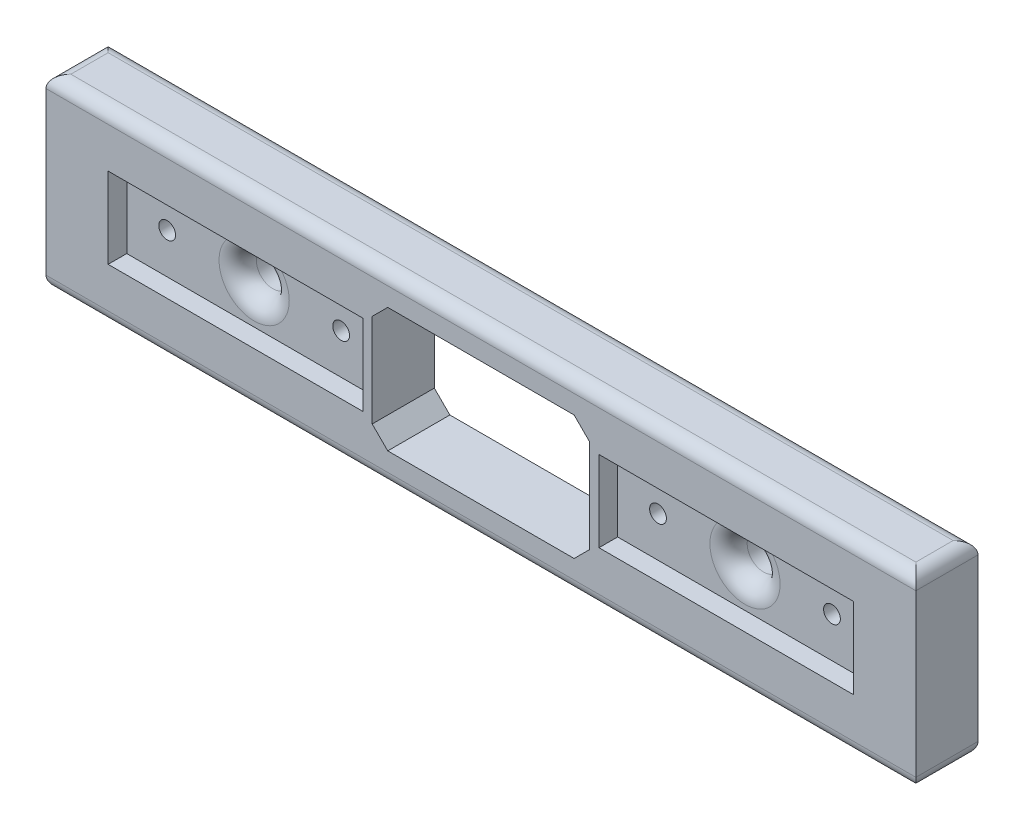
SolidWorks part; units mm, degrees
ref_plane "Front Plane" through (0, 0, 0) normal (0, 0, 1) x (1, 0, 0)
ref_plane "Top Plane" through (0, 0, 0) normal (0, 1, 0) x (1, 0, 0)
ref_plane "Right Plane" through (0, 0, 0) normal (1, 0, 0) x (0, 0, -1)
sketch "Sketch1" plane through (0, 0, 0) normal (0, 0, 1) x (1, 0, 0)
  line L1 (-70, -15) -> (70, -15)
  line L2 (-70, -15) -> (-70, 15)
  line L3 (-70, 15) -> (70, 15)
  line L4 (70, -15) -> (70, 15)
  line L5 (-70, -15) -> (70, 15) construction
  line L6 (-70, 15) -> (70, -15) construction
  line L7 (-17.5, -10) -> (17.5, -10)
  line L8 (-17.5, -10) -> (-17.5, 10)
  line L9 (-17.5, 10) -> (17.5, 10)
  line L10 (17.5, -10) -> (17.5, 10)
  line L11 (-17.5, -10) -> (17.5, 10) construction
  line L12 (-17.5, 10) -> (17.5, -10) construction
  point P0 (0, 0)
  point P5 (0, 0)
  dimension "D3" = 20
  dimension "D1" = 140
  dimension "D2" = 30
  dimension "D4" = 35
extrude "Boss-Extrude1" add sketch "Sketch1" along normal mid plane 10
sketch "Sketch5" plane through (0, 0, 5) normal (0, 0, 1) x (1, 0, 0)
  line L0 (-70, 15) -> (-70, -15) construction
  line L1 (-19, -6.5) -> (-60, -6.5)
  line L2 (-19, -6.5) -> (-19, 6.5)
  line L3 (-19, 6.5) -> (-60, 6.5)
  line L4 (-60, -6.5) -> (-60, 6.5)
  line L5 (-19, -6.5) -> (-60, 6.5) construction
  line L6 (-19, 6.5) -> (-60, -6.5) construction
  point P0 (-39.5, 0)
  dimension "D1" = 13
  dimension "D2" = 41
  dimension "D3" = 10
extrude "Cut-Extrude3" cut sketch "Sketch5" against normal blind 3
sketch "Sketch6" plane through (0, 0, 2) normal (0, 0, 1) x (1, 0, 0)
  line L1 (-39.5, 0) -> (-39.5, -6.5) construction
  line L3 (-60, -6.5) -> (-19, -6.5) construction
  circle A0 centre (-39.5, 0) radius 2.65
  circle A1 centre (-25.5, 0) radius 1.35
  circle A2 centre (-53.5, 0) radius 1.35
  dimension "D1" = 5.3
  dimension "D2" = 2.7
  dimension "D4" = 14
extrude "Cut-Extrude4" cut sketch "Sketch6" against normal through all
sketch "Sketch7" plane through (0, 0, -5) normal (0, 0, -1) x (-1, 0, 0)
  line L0 (39.5, 0) -> (39.5, -5.4696) construction
  circle A0 centre (53.5, 0) radius 2.75
  circle A1 centre (25.5, 0) radius 2.75
  dimension "D1" = 5.5
extrude "Cut-Extrude5" cut sketch "Sketch7" against normal blind 2
fillet "Fillet1" radius 3 1 edges at (-36.85, 0, 2)
mirror "Mirror11" about plane through (0, 0, 0) normal (1, 0, 0) of "Cut-Extrude5", "Cut-Extrude3", "Fillet1", "Cut-Extrude4"
fillet "Fillet2" radius 2 8 edges at (-70, -15, 0) (0, -15, 5) (70, -15, 0) (0, -15, -5) (70, 15, 0) (0, 15, 5) (-70, 15, 0) (0, 15, -5)
chamfer "Chamfer1" distance 2.5 angle 45 4 edges at (-17.5, 10, 0) (-17.5, -10, 0) (17.5, -10, 0) (17.5, 10, 0)
